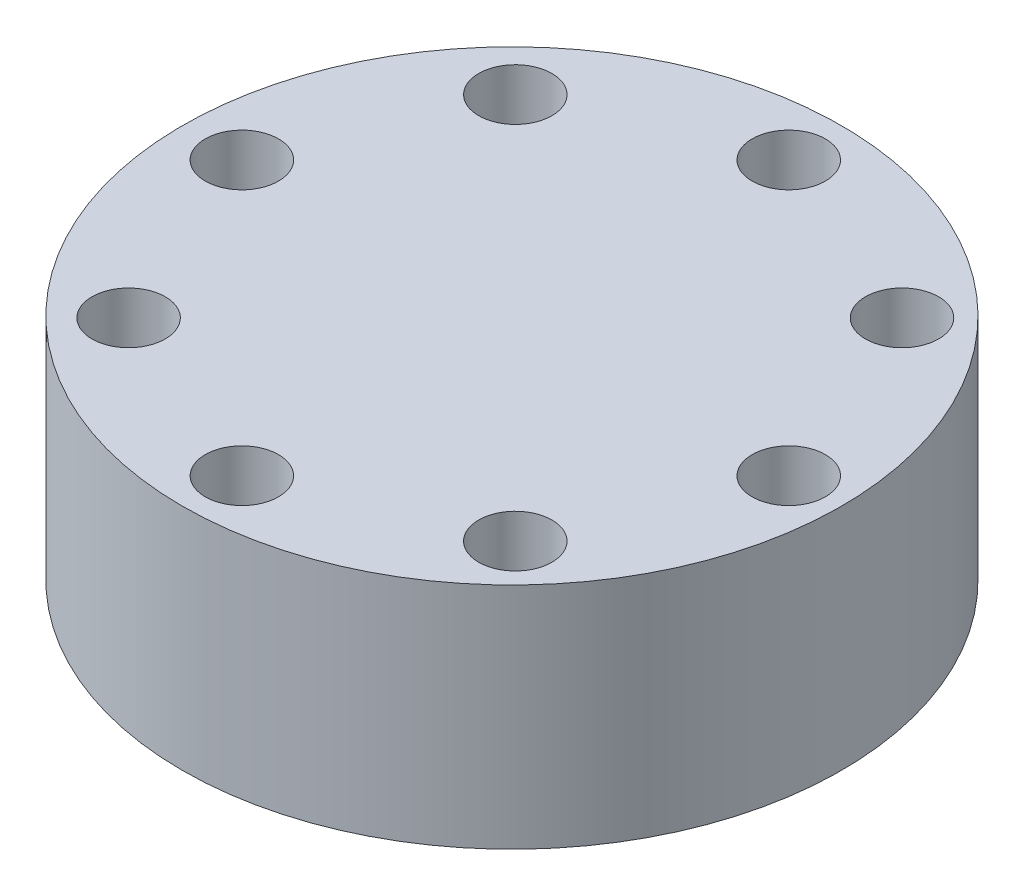
SolidWorks part; units mm, degrees
ref_plane "Front Plane" through (0, 0, 0) normal (0, 0, 1) x (1, 0, 0)
ref_plane "Top Plane" through (0, 0, 0) normal (0, 1, 0) x (1, 0, 0)
ref_plane "Right Plane" through (0, 0, 0) normal (1, 0, 0) x (0, 0, -1)
sketch "Sketch1" plane through (0, 0, 0) normal (0, 1, 0) x (1, 0, 0)
  circle A0 centre (0, 0) radius 36
  dimension "D1" = 72
extrude "Boss-Extrude1" add sketch "Sketch1" along normal blind 25
sketch "Sketch2" plane through (0, 25, 0) normal (0, 1, 0) x (1, 0, 0)
  circle A0 centre (0, 0) radius 29.5
  dimension "D1" = 59
sketch "Sketch3" plane through (0, 25, 0) normal (0, 1, 0) x (1, 0, 0)
  circle A0 centre (-29.5, 0) radius 4
  circle A1 centre (0, 0) radius 29.5 construction
  dimension "D1" = 8
extrude "Cut-Extrude1" cut sketch "Sketch3" against normal through all contours A0
pattern_circular "CirPattern1" count 8 over 360 about axis through (0.3687, 0, 0) along (0, 1, 0) of "Cut-Extrude1"
